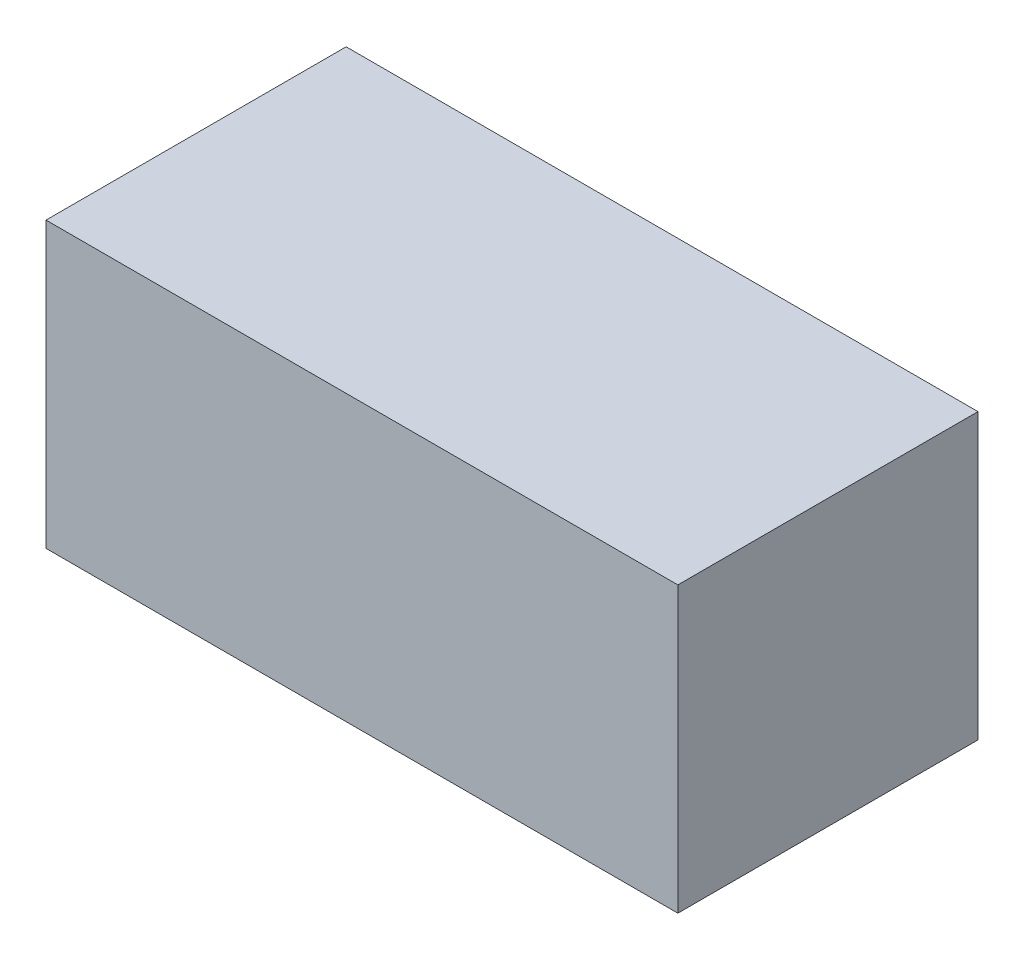
SolidWorks part; units mm, degrees
ref_plane "前视基准面" through (0, 0, 0) normal (0, 0, 1) x (1, 0, 0)
ref_plane "上视基准面" through (0, 0, 0) normal (0, 1, 0) x (1, 0, 0)
ref_plane "右视基准面" through (0, 0, 0) normal (1, 0, 0) x (0, 0, -1)
sketch "草图1" plane through (0, 0, 0) normal (0, 1, 0) x (1, 0, 0)
  line L1 (0, 0) -> (200, 0)
  line L2 (0, 0) -> (0, 95)
  line L3 (0, 95) -> (200, 95)
  line L4 (200, 0) -> (200, 95)
  dimension "D1" = 95
  dimension "D2" = 200
extrude "凸台-拉伸1" add sketch "草图1" along normal blind 90 contours L2 L1 L4 L3
sketch "草图2" plane through (0, 0, 0) normal (0, -1, 0) x (-1, 0, 0)
  line L0 (0, 0) -> (0, 95) construction
  line L1 (0, 0) -> (-200, 0) construction
  circle A0 centre (-50, 47.5) radius 30
  dimension "D2" = 47.5
  dimension "D3" = 60
  dimension "D1" = 50
extrude "切除-拉伸1" cut sketch "草图2" against normal blind 10
